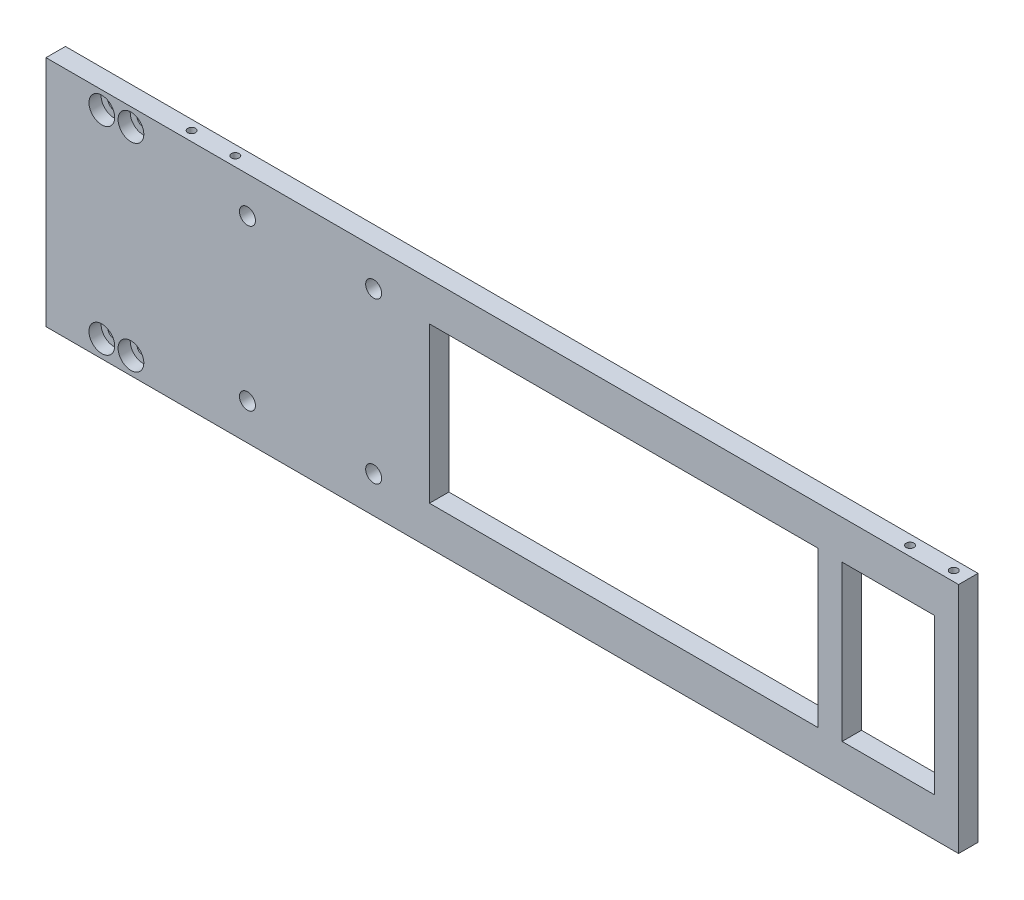
SolidWorks part; units mm, degrees
material "1060 Alloy"
ref_plane "Front Plane" through (0, 0, 0) normal (0, 0, 1) x (1, 0, 0)
ref_plane "Top Plane" through (0, 0, 0) normal (0, 1, 0) x (1, 0, 0)
ref_plane "Right Plane" through (0, 0, 0) normal (1, 0, 0) x (0, 0, -1)
sketch "Sketch1" plane through (0, 0, 0) normal (0, 0, 1) x (1, 0, 0)
  line L1 (-94, -24) -> (94, -24)
  line L2 (-94, -24) -> (-94, 24)
  line L3 (-94, 24) -> (94, 24)
  line L4 (94, -24) -> (94, 24)
  line L5 (-94, -24) -> (94, 24) construction
  line L6 (-94, 24) -> (94, -24) construction
  point P0 (0, 0)
  dimension "D1" = 48
  dimension "D2" = 188
extrude "Boss-Extrude1" add sketch "Sketch1" along normal blind 4
sketch "Sketch2" plane through (0, 0, 0) normal (0, 0, -1) x (-1, 0, 0)
  line L0 (63.5, -20.4) -> (94, -20.4) construction
  line L1 (94, 24) -> (94, -24) construction
  line L2 (67.5, -22.5) -> (67.5, 22.5) construction
  line L3 (94, -24) -> (-94, -24) construction
  circle A0 centre (76.5, -20.4) radius 1.25
  circle A1 centre (82.5, -20.4) radius 1.25
  dimension "D1" = 2.5
  dimension "D2" = 9
  dimension "D4" = 3.6
  dimension "D3" = 2
extrude "Cut-Extrude1" cut sketch "Sketch2" against normal up to surface (4 mm away) up to face at (0, 0, 4)
sketch "Sketch3" plane through (0, 0, 0) normal (0, 0, -1) x (-1, 0, 0)
  circle A0 centre (76.5, -20.4) radius 2.65
  circle A1 centre (82.5, -20.4) radius 2.65
  dimension "D1" = 5.3
  dimension "D2" = 5.3
extrude "Cut-Extrude2" cut sketch "Sketch3" against normal blind 10 from offset 1.5 offset against normal yes
ref_plane "Plane1" through (0, 0, 0) normal (0, -1, 0) x (-1, 0, 0)
mirror "Mirror1" about plane through (0, 0, 0) normal (0, -1, 0) of "Cut-Extrude2", "Cut-Extrude1"
sketch "Sketch4" plane through (0, 0, 4) normal (0, 0, 1) x (1, 0, 0)
  line L0 (94, 24) -> (-94, 24) construction
  line L1 (-94, 24) -> (-94, -24) construction
  circle A0 centre (-52.5, 18) radius 2
  circle A1 centre (-26.5, 18) radius 2
  dimension "D2" = 4
  dimension "D5" = 4
  dimension "D1" = 6
  dimension "D3" = 41.5
  dimension "D4" = 26
  dimension "D6" = 6
extrude "Cut-Extrude3" [suppressed] cut sketch "Sketch4" against normal up to surface (3 mm away)
mirror "Mirror2" [suppressed] about plane through (0, 0, 0) normal (0, -1, 0)
sketch "Sketch5" plane through (0, 24, 0) normal (0, 1, 0) x (1, 0, 0)
  line L0 (-94, -4) -> (-94, 0) construction
  line L2 (94, 0) -> (-94, 0) construction
  point P0 (-66, -2)
  point P1 (-57, -2)
  point P3 (82, -2)
  point P5 (91, -2)
  dimension "D1" = 28
  dimension "D2" = 2
  dimension "D3" = 9
  dimension "D4" = 139
  dimension "D5" = 9
hole_wizard "M2 Tapped Hole1" positions "Sketch6" profile "Sketch7" tap size "M2" standard "ISO"
sketch "Sketch6" plane through (0, 24, 0) normal (0, 1, 0) x (1, 0, 0)
  point P0 (-66, -2)
  point P3 (-57, -2)
  point P6 (82, -2)
  point P9 (91, -2)
sketch "Sketch7" plane through (-66, 24, 2) normal (1, 0, 0) x (0, 0, 1)
  line L0 (0, 0) -> (0, 6.4807)
  line L1 (0, 6.4807) -> (0.8, 6)
  line L2 (0.8, 6) -> (0.8, 0)
  line L5 (0.8, 0) -> (0, 0)
  line L10 (0, 6.4807) -> (-0.8, 6) construction
  line L11 (0, -6.35) -> (0, 107.95) construction
  dimension "Tap Drill Dia." = 1.6
  dimension "Tap Drill Depth" = 6
  dimension "Drill Angle" = 118
cosmetic thread "Hole Thread5" parameters "D1"=6, "D2"=2
cosmetic thread "Hole Thread6" parameters "D1"=6, "D2"=2
cosmetic thread "Hole Thread7" parameters "D1"=6, "D2"=2
cosmetic thread "Hole Thread8" parameters "D1"=6, "D2"=2
ref_plane "Plane2" through (0, 0, 0) normal (0, 1, 0) x (1, 0, 0)
mirror "Mirror3" about plane through (0, 0, 0) normal (0, 1, 0) of "M2 Tapped Hole1"
sketch "Sketch8" plane through (0, 0, 4) normal (0, 0, 1) x (1, 0, 0)
  line L1 (89, 16) -> (70, 16)
  line L2 (89, 16) -> (89, -16)
  line L3 (89, -16) -> (70, -16)
  line L4 (70, 16) -> (70, -16)
  line L5 (79, 26) -> (94, 26) construction
  line L6 (79, -26) -> (94, -26) construction
  line L7 (94, -24) -> (94, 24) construction
  point P7 (86.5, 26)
  dimension "D1" = 10
  dimension "D2" = 10
  dimension "D3" = 19
  dimension "D4" = 5
extrude "Cut-Extrude4" cut sketch "Sketch8" against normal up to surface (4 mm away) and the other way through all up to face at (-83.75, 20.4, 0)
sketch "Sketch9" plane through (0, 0, 4) normal (0, 0, 1) x (1, 0, 0)
  line L0 (94, 24) -> (-94, 24) construction
  line L1 (65, 16) -> (-15, 16)
  line L2 (65, 16) -> (65, -16)
  line L3 (65, -16) -> (-15, -16)
  line L4 (-15, 16) -> (-15, -16)
  line L5 (-94, -24) -> (94, -24) construction
  line L6 (70, -16) -> (70, 16) construction
  dimension "D1" = 8
  dimension "D2" = 8
  dimension "D3" = 80
  dimension "D4" = 5
extrude "Cut-Extrude5" cut sketch "Sketch9" against normal up to surface (4 mm away) up to face at (79.5, 0, 0)
sketch "Sketch10" plane through (0, 0, 4) normal (0, 0, 1) x (1, 0, 0)
  line L0 (-94, -24) -> (94, -24) construction
  line L1 (-94, 24) -> (-94, -24) construction
  point P0 (-52.5, 16.5)
  point P1 (-26.5, 16.5)
  point P2 (0, 0)
  point P3 (-26.5, -16.5)
  point P4 (0, 0)
  point P5 (-52.5, -16.5)
  point P6 (0, 0)
  point P7 (0, 0)
  point P8 (0, 0)
  point P11 (0, 0)
  point P12 (0, 0)
  dimension "D1" = 33
  dimension "D2" = 41.5
  dimension "D3" = 7.5
  dimension "D4" = 41.5
  dimension "D7" = 26
hole_wizard "M4 Tapped Hole1" positions "Sketch11" profile "Sketch12" tap size "M4" standard "ISO"
sketch "Sketch11" plane through (0, 0, 4) normal (0, 0, 1) x (1, 0, 0)
  point P0 (-52.5, 16.5)
  point P3 (-26.5, 16.5)
  point P6 (-26.5, -16.5)
  point P9 (-52.5, -16.5)
  point P12 (0, 0)
sketch "Sketch12" plane through (-52.5, 16.5, 4) normal (1, 0, 0) x (0, -1, 0)
  line L0 (0, 0) -> (0, 4.9904)
  line L1 (0, 4.9904) -> (1.65, 3.999)
  line L2 (1.65, 3.999) -> (1.65, 0)
  line L5 (1.65, 0) -> (0, 0)
  line L10 (0, 4.9904) -> (-1.65, 3.999) construction
  line L11 (0, -6.35) -> (0, 107.95) construction
  dimension "Tap Drill Dia." = 3.3
  dimension "Tap Drill Depth" = 3.999
  dimension "Drill Angle" = 118
cosmetic thread "Hole Thread1" parameters "D1"=3, "D2"=4
cosmetic thread "Hole Thread2" parameters "D1"=3, "D2"=4
cosmetic thread "Hole Thread3" parameters "D1"=3, "D2"=4
cosmetic thread "Hole Thread4" parameters "D1"=3, "D2"=4
equation "\"D2@Sketch9\"=\"D1@Sketch9\""
